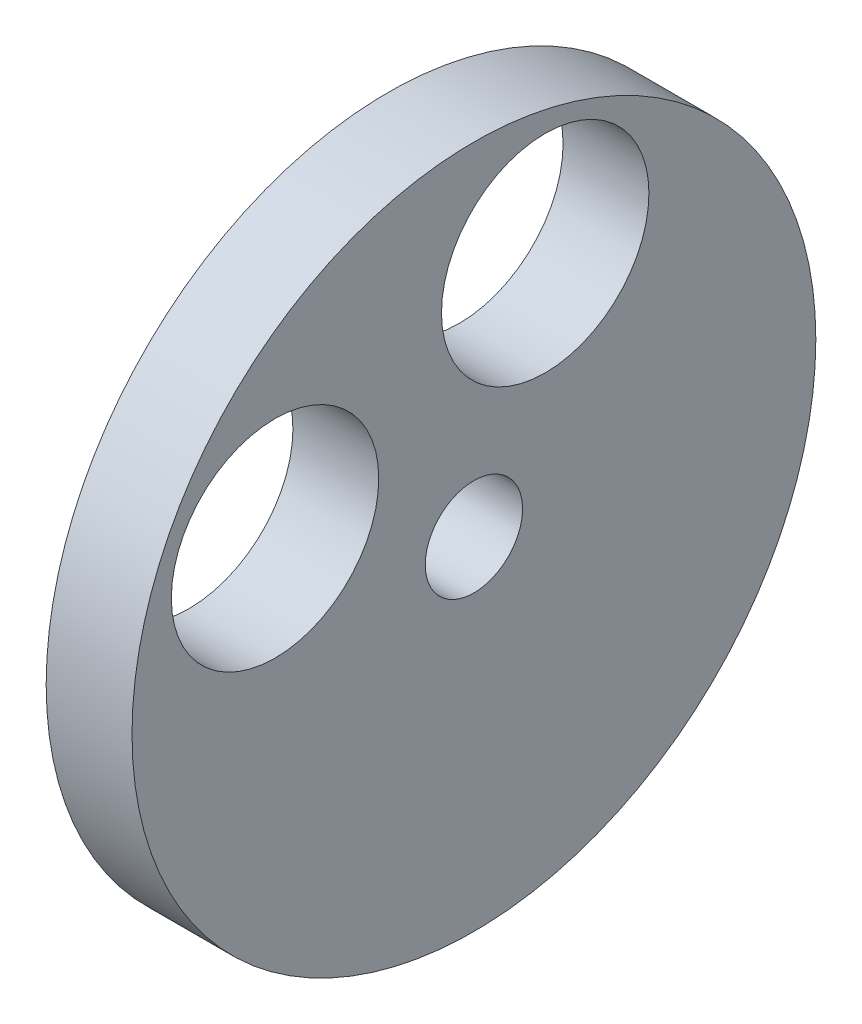
SolidWorks part; units mm, degrees
material "Alumina"
ref_plane "Front Plane" through (0, 0, 0) normal (0, 0, 1) x (1, 0, 0)
ref_plane "Top Plane" through (0, 0, 0) normal (0, 1, 0) x (1, 0, 0)
ref_plane "Right Plane" through (0, 0, 0) normal (1, 0, 0) x (0, 0, -1)
sketch "Axial profile (mm)" plane through (0, 0, 0) normal (0, 0, 1) x (1, 0, 0)
  line L0 (-110, 0) -> (75, 0) construction
  line L1 (80, 3.4) -> (86, 3.4)
  line L2 (86, 3.4) -> (86, 23.9)
  line L3 (86, 23.9) -> (80, 23.9)
  line L4 (80, 23.9) -> (80, 3.4)
revolve "Full revolution" add sketch "Axial profile (mm)" angle 360 about L0
sketch "Sketch2" plane through (0, 0, 0) normal (1, 0, 0) x (0, 0, -1)
  circle A0 centre (4.9831, 14.6772) radius 7.25
  circle A1 centre (-13.9019, 6.8548) radius 7.25
extrude "Axial holes" cut sketch "Sketch2" along normal through all and the other way through all
